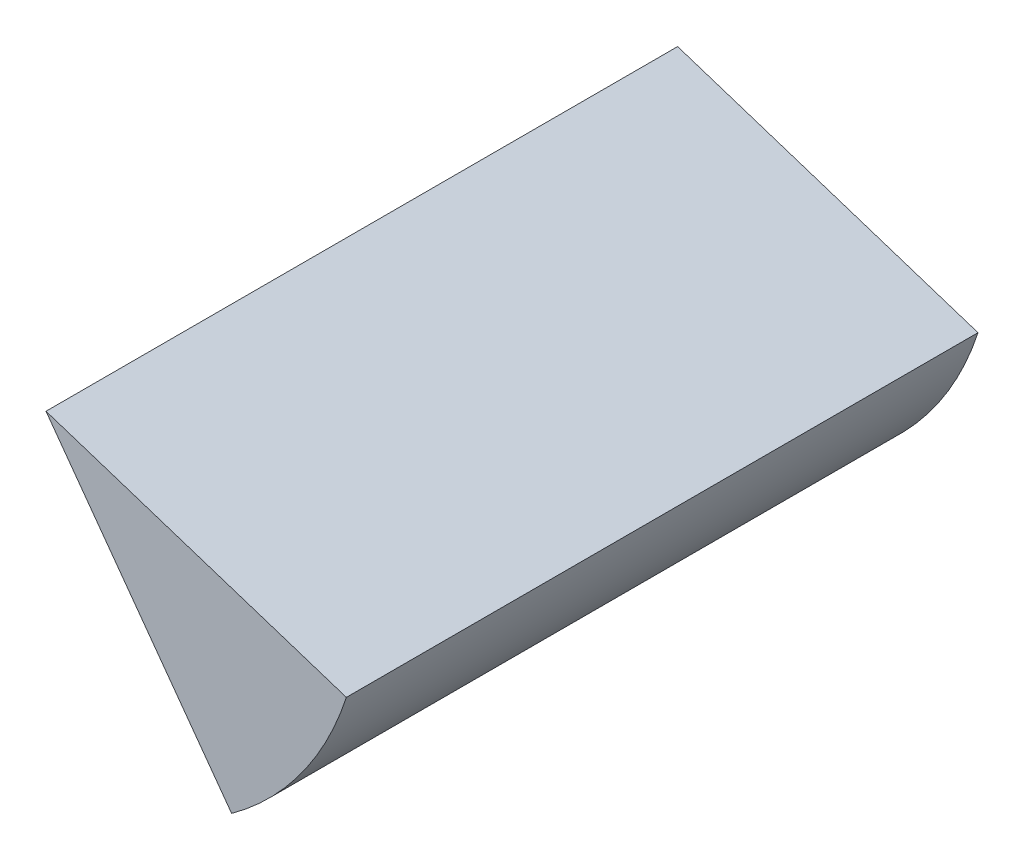
SolidWorks part; units mm, degrees
ref_plane "Alzado" through (0, 0, 0) normal (0, 0, 1) x (1, 0, 0)
ref_plane "Planta" through (0, 0, 0) normal (0, 1, 0) x (1, 0, 0)
ref_plane "Vista lateral" through (0, 0, 0) normal (1, 0, 0) x (0, 0, -1)
sketch "Croquis1" plane through (0, 0, 0) normal (0, 0, 1) x (1, 0, 0)
  line L1 (0, 0) -> (14.6946, -20.2254)
  line L2 (0, 0) -> (23.7764, -7.7254)
  arc A0 (14.6946, -20.2254) -> (23.7764, -7.7254) centre (0, 0) ccw
  dimension "D1" = 50
  dimension "D3" = 36
extrude "Saliente-Extruir1" add sketch "Croquis1" along normal blind 50
sketch "Croquis2" plane through (0, 0, 0) normal (0, 0, -1) x (-1, 0, 0)
  circle A0 centre (-15.3849, -10.8874) radius 5.0222
extrude "Cortar-Extruir1" cut sketch "Croquis2" against normal blind 10 contours A0
